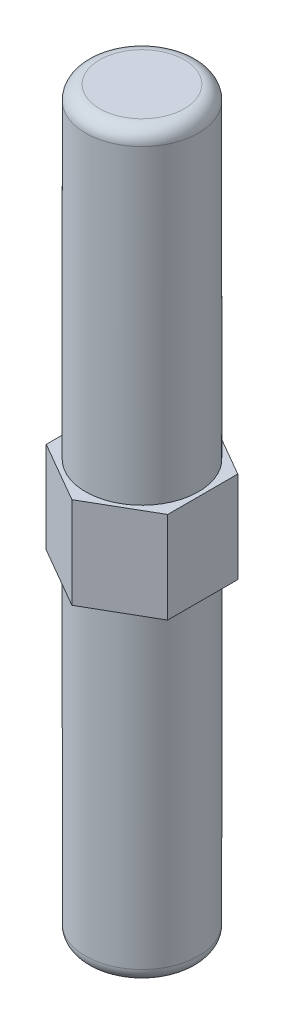
SolidWorks part; units mm, degrees
ref_plane "Front Plane" through (0, 0, 0) normal (0, 0, 1) x (1, 0, 0)
ref_plane "Top Plane" through (0, 0, 0) normal (0, 1, 0) x (1, 0, 0)
ref_plane "Right Plane" through (0, 0, 0) normal (1, 0, 0) x (0, 0, -1)
sketch "Sketch1" plane through (0, 0, 0) normal (0, 1, 0) x (1, 0, 0)
  line L0 (0, 0) -> (0, -3.1529) construction
  line L1 (-2.7305, -1.5765) -> (0, -3.1529)
  line L2 (0, -3.1529) -> (2.7305, -1.5765)
  line L3 (2.7305, -1.5765) -> (2.7305, 1.5765)
  line L4 (2.7305, 1.5765) -> (0, 3.1529)
  line L5 (0, 3.1529) -> (-2.7305, 1.5765)
  line L6 (-2.7305, 1.5765) -> (-2.7305, -1.5765)
  circle A0 centre (0, 0) radius 2.7305 construction
  dimension "D1" = 5.461
extrude "Boss-Extrude1" add sketch "Sketch1" along normal mid plane 4.1148 contours L2 L3 L4 L5 L6 L1
sketch "Sketch2" plane through (0, 2.0574, 0) normal (0, 1, 0) x (1, 0, 0)
  circle A0 centre (0, 0) radius 2.54
  dimension "D1" = 5.08
extrude "Boss-Extrude2" add sketch "Sketch2" along normal blind 14.605
mirror "Mirror1" about plane through (0, 0, 0) normal (0, 1, 0) of "Boss-Extrude2"
fillet "Fillet1" radius 0.635 2 edges at (0, -16.6624, 2.54) (0, 16.6624, 2.54)
